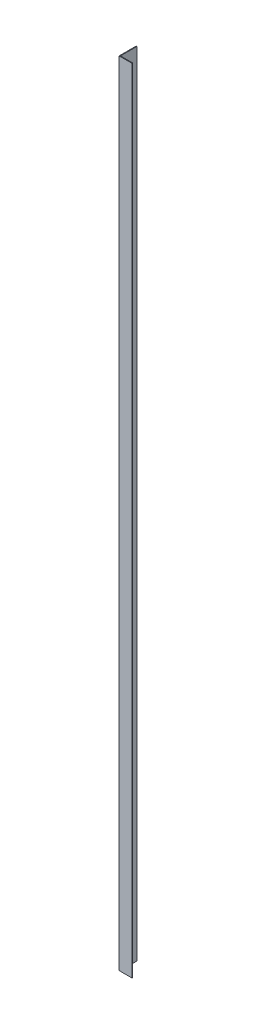
SolidWorks part; units mm, degrees
ref_plane "Front Plane" through (0, 0, 0) normal (0, 0, 1) x (1, 0, 0)
ref_plane "Top Plane" through (0, 0, 0) normal (0, 1, 0) x (1, 0, 0)
ref_plane "Right Plane" through (0, 0, 0) normal (1, 0, 0) x (0, 0, -1)
other "Configuration Table"
sketch "Sketch1" plane through (0, 0, 0) normal (0, 1, 0) x (1, 0, 0)
  line L0 (700, -40) -> (700, -38.5)
  line L1 (700, -38.5) -> (671.5, -38.5)
  line L2 (671.5, -38.5) -> (671.5, 0)
  line L3 (671.5, 0) -> (670, 0)
  line L4 (670, 0) -> (670, -40)
  line L5 (670, -40) -> (700, -40)
extrude "PACK_sove_sag_1" add sketch "Sketch1" along normal blind 1850 from offset 120 separate body
